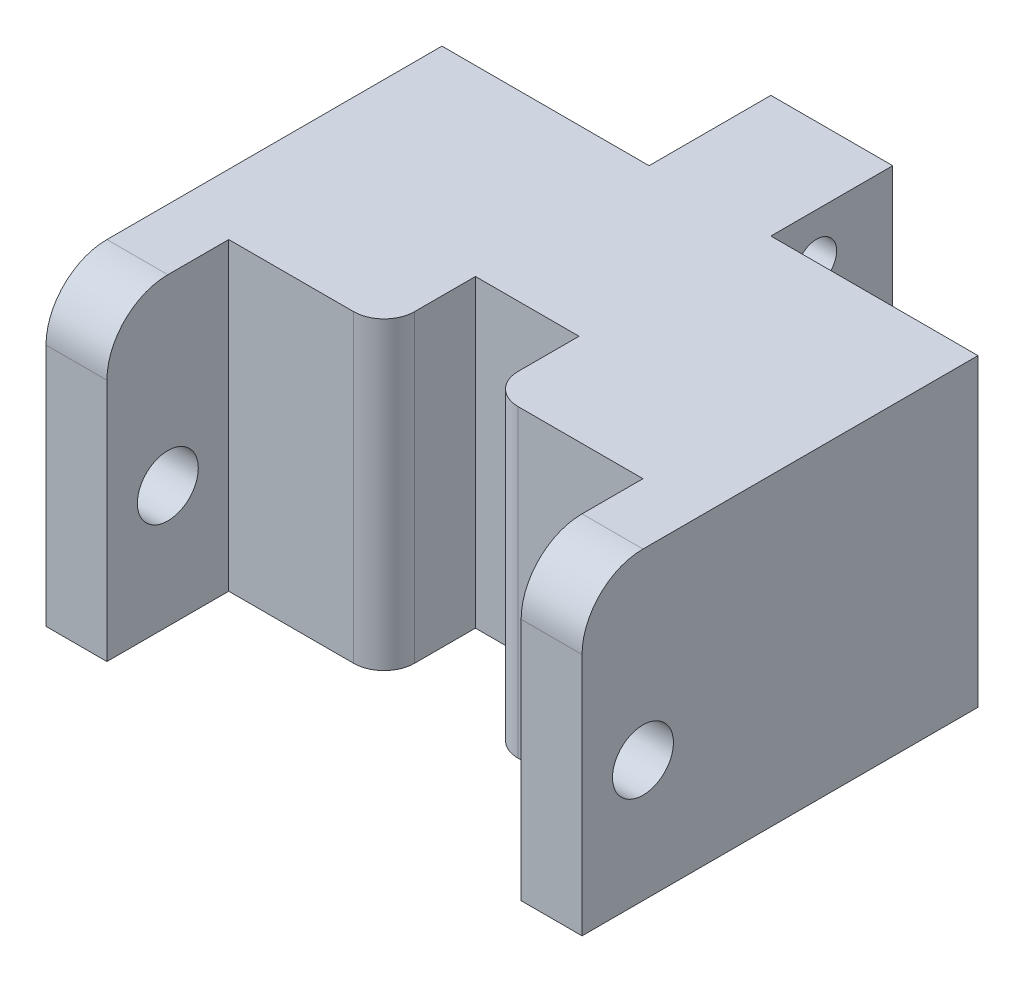
SolidWorks part; units mm, degrees
ref_plane "Front Plane" through (0, 0, 0) normal (0, 0, 1) x (1, 0, 0)
ref_plane "Top Plane" through (0, 0, 0) normal (0, 1, 0) x (1, 0, 0)
ref_plane "Right Plane" through (0, 0, 0) normal (1, 0, 0) x (0, 0, -1)
sketch "Sketch1" plane through (0, 0, 0) normal (0, 1, 0) x (1, 0, 0)
  line L0 (20, 0) -> (0, 0)
  line L1 (20, 0) -> (20, -20)
  line L2 (20, -20) -> (54, -20)
  line L3 (54, -20) -> (54, -85)
  line L4 (54, -85) -> (44, -85)
  line L5 (44, -85) -> (44, -65)
  line L6 (-24, -65) -> (1.5, -65)
  line L7 (-24, -65) -> (-24, -85)
  line L8 (-24, -85) -> (-34, -85)
  line L9 (-34, -85) -> (-34, -20)
  line L10 (-34, -20) -> (0, -20)
  line L11 (0, -20) -> (0, 0)
  line L12 (0, 0) -> (13.4583, 0) construction
  line L13 (44, -65) -> (18.5, -65)
  line L14 (1.5, -65) -> (1.5, -50)
  line L15 (1.5, -50) -> (18.5, -50)
  line L16 (18.5, -50) -> (18.5, -65)
  dimension "D1" = 34
  dimension "D2" = 20
  dimension "D3" = 34
  dimension "D4" = 65
  dimension "D5" = 65
  dimension "D6" = 10
  dimension "D7" = 10
  dimension "D8" = 20
  dimension "D9" = 20
  dimension "D10" = 0
  dimension "D11" = 0
  dimension "D12" = 25.5
  dimension "D13" = 25.5
  dimension "D14" = 15
extrude "Boss-Extrude2" add sketch "Sketch1" along normal blind 50 contours L6 L14 L15 L16 L13 L5 L4 L3 L2 L1 L0 L11 L10 L9 L8 L7
fillet "Fillet3" radius 10 1 edges at (-29, 50, 85)
fillet "Fillet4" radius 10 1 edges at (49, 50, 85)
fillet "Fillet5" radius 5 1 edges at (1.5, 25, 65)
fillet "Fillet6" radius 5 1 edges at (18.5, 25, 65)
ref_plane "Plane1" through (-34, 0, 0) normal (-1, 0, 0) x (0, 0, 1)
sketch "Sketch2" plane through (-34, 0, 0) normal (-1, 0, 0) x (0, 0, 1)
  line L0 (85, 0) -> (20, 0) construction
  line L1 (85, 40) -> (85, 0) construction
  circle A0 centre (75, 20) radius 5
  dimension "D1" = 10
  dimension "D2" = 20
  dimension "D3" = 10
ref_plane "Plane2" through (0, 0, 0) normal (-1, 0, 0) x (0, 0, 1)
sketch "Sketch3" plane through (0, 0, 0) normal (-1, 0, 0) x (0, 0, 1)
  line L0 (20, 50) -> (20, 0) construction
  line L1 (0, 0) -> (20, 0)
  line L2 (0, 0) -> (0, 15)
  line L3 (0, 15) -> (20, 15)
  line L4 (20, 0) -> (20, 15)
  dimension "D1" = 15
extrude "Cut-Extrude2" cut sketch "Sketch3" against normal blind 37
extrude "Cut-Extrude3" cut sketch "Sketch2" against normal blind 115 contours A0
sketch "Sketch4" plane through (0, 0, 0) normal (-1, 0, 0) x (0, 0, 1)
  circle A0 centre (12.5, 42.5) radius 3.3
  circle A1 centre (12.5, 27.5) radius 3.3
  dimension "D4" = 6.6
  dimension "D5" = 6.6
extrude "Cut-Extrude4" cut sketch "Sketch4" against normal up to next
